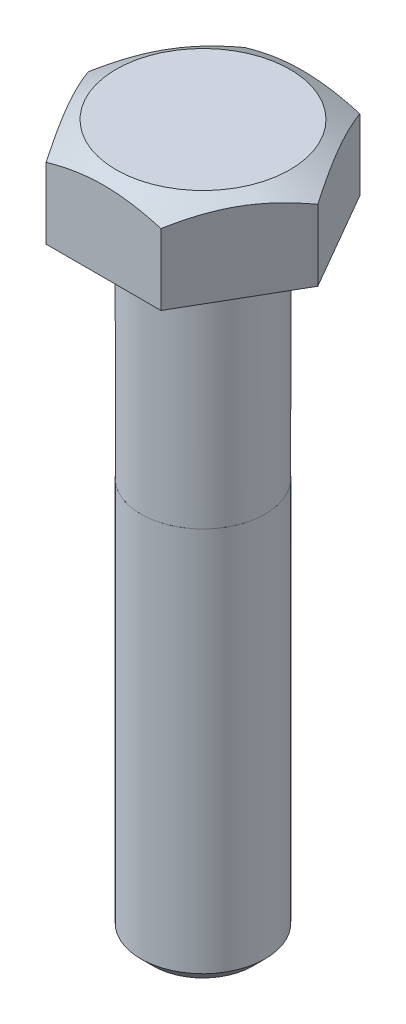
SolidWorks part; units mm, degrees
ref_plane "Front Plane" through (0, 0, 0) normal (0, 0, 1) x (1, 0, 0)
ref_plane "Top Plane" through (0, 0, 0) normal (0, 1, 0) x (1, 0, 0)
ref_plane "Right Plane" through (0, 0, 0) normal (1, 0, 0) x (0, 0, -1)
sketch "Sketch1" plane through (0, 0, 0) normal (0, 1, 0) x (1, 0, 0)
  line L1 (-4.6188, 0) -> (-2.3094, -4)
  line L2 (-2.3094, -4) -> (2.3094, -4)
  line L3 (2.3094, -4) -> (4.6188, 0)
  line L4 (4.6188, 0) -> (2.3094, 4)
  line L5 (2.3094, 4) -> (-2.3094, 4)
  line L6 (-2.3094, 4) -> (-4.6188, 0)
  circle A0 centre (0, 0) radius 4 construction
  dimension "D1" = 8
extrude "Boss-Extrude1" add sketch "Sketch1" against normal blind 3.5
sketch "Sketch2" plane through (0, 0, 0) normal (0, 1, 0) x (1, 0, 0)
  circle A0 centre (0, 0) radius 3.5
  circle A1 centre (0, 0) radius 4 construction
  dimension "D1" = 0.5
extrude "Cut-Extrude1" cut sketch "Sketch2" against normal through all both draft 60 and the other way through all flip side to cut
sketch "Sketch3" plane through (0, -3.5, 0) normal (0, -1, 0) x (1, 0, 0)
  circle A0 centre (0, 0) radius 2.5
  dimension "D1" = 5
extrude "Boss-Extrude2" add sketch "Sketch3" along normal blind 9
sketch "Sketch4" plane through (0, -12.5, 0) normal (0, -1, 0) x (1, 0, 0)
  circle A0 centre (0, 0) radius 2.5
  circle A1 centre (0, 0) radius 2.5 construction
extrude "Boss-Extrude3" add sketch "Sketch4" along normal blind 16 separate body
chamfer "Chamfer1" distance 0.5 angle 45 1 edges at (0, -28.5, -2.5)
